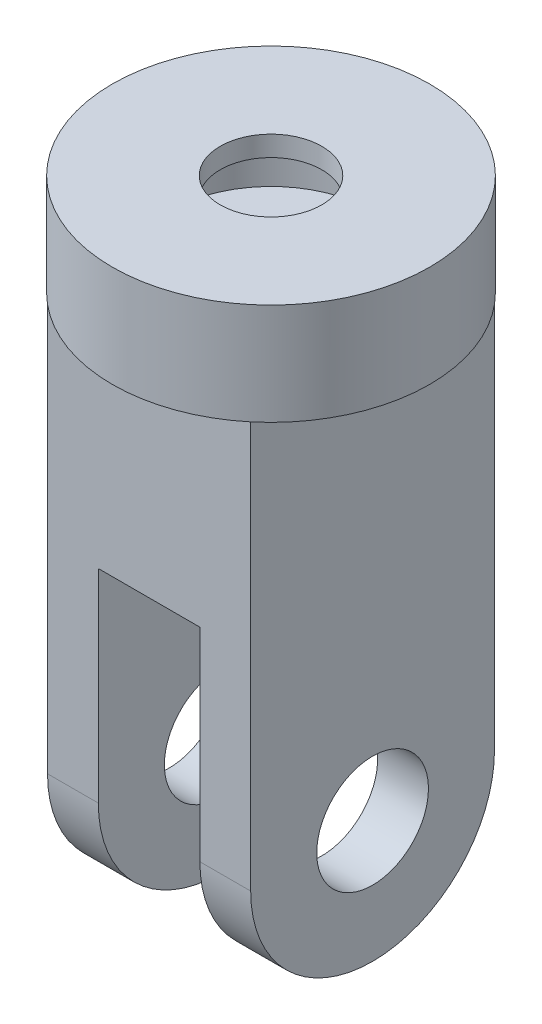
SolidWorks part; units mm, degrees
ref_plane "Front Plane" through (0, 0, 0) normal (1, 0, 0) x (0, 1, 0)
ref_plane "Top Plane" through (0, 0, 0) normal (0, 0, 1) x (0, 1, 0)
ref_plane "Right Plane" through (0, 0, 0) normal (0, 1, 0) x (-1, 0, 0)
sketch "Sketch1" plane through (0, 0, 0) normal (1, 0, 0) x (0, 1, 0)
  line L0 (0, 6) -> (20, 6)
  line L1 (20, 6) -> (20, -6)
  line L2 (20, -6) -> (0, -6)
  arc A0 (0, 6) -> (0, -6) centre (0, 0) ccw
  circle A1 centre (0, 0) radius 2.75
  dimension "D1" = 12
  dimension "D2" = 5.5
  dimension "D3" = 20
extrude "Boss-Extrude1" add sketch "Sketch1" along normal blind 10
sketch "Sketch3" plane through (0, 20, 0) normal (0, 1, 0) x (-1, 0, 0)
  line L0 (-5, 6) -> (-5, -8.8619) construction
  line L1 (-10, 6) -> (0, 6) construction
  line L2 (0, 0) -> (-10.6163, 0) construction
  circle A0 centre (-5, 0) radius 7.8102
  circle A1 centre (-5, 0) radius 5
  dimension "D1" = 10
extrude "Boss-Extrude3" add sketch "Sketch3" along normal blind 5 contours A0
sketch "Sketch4" plane through (0, 25, 0) normal (0, 1, 0) x (-1, 0, 0)
  line L0 (-5, 7.8102) -> (-5, -7.8102) construction
  circle A0 centre (-5, 0) radius 7.8102 construction
  circle A1 centre (-5, 0) radius 5
  dimension "D1" = 10
extrude "Cut-Extrude1" cut sketch "Sketch4" against normal blind 4
sketch "Sketch5" plane through (0, 25, 0) normal (0, 1, 0) x (-1, 0, 0)
  line L0 (-12.8102, 0) -> (2.8102, 0) construction
  circle A0 centre (-5, 0) radius 7.8102 construction
  circle A1 centre (-5, 0) radius 6.1288
  circle A2 centre (-5, 0) radius 2.5
  dimension "D1" = 5
extrude "Boss-Extrude4" add sketch "Sketch5" against normal blind 1
sketch "Sketch7" plane through (0, 0, 0) normal (0, 0, 1) x (0, 1, 0)
  line L1 (10, -2.5) -> (-10.888, -2.5)
  line L3 (10, -7.5) -> (-10.888, -7.5)
  line L4 (-10.888, -2.5) -> (-10.888, -7.5)
  line L5 (20, 0) -> (0, 0) construction
  line L6 (8.5473, -2.5) -> (8.5155, -2.5)
  line L8 (8.5473, 0) -> (8.5155, 0)
  line L10 (20, -10) -> (0, -10) construction
  line L12 (10, -2.5) -> (10, -7.5)
  line L13 (20, -10) -> (20, 0) construction
  dimension "D1" = 2.5
  dimension "D2" = 2.5
  dimension "D3" = 10
extrude "Cut-Extrude2" cut sketch "Sketch7" along normal mid plane 26 contours L4 L3 L12 L1
